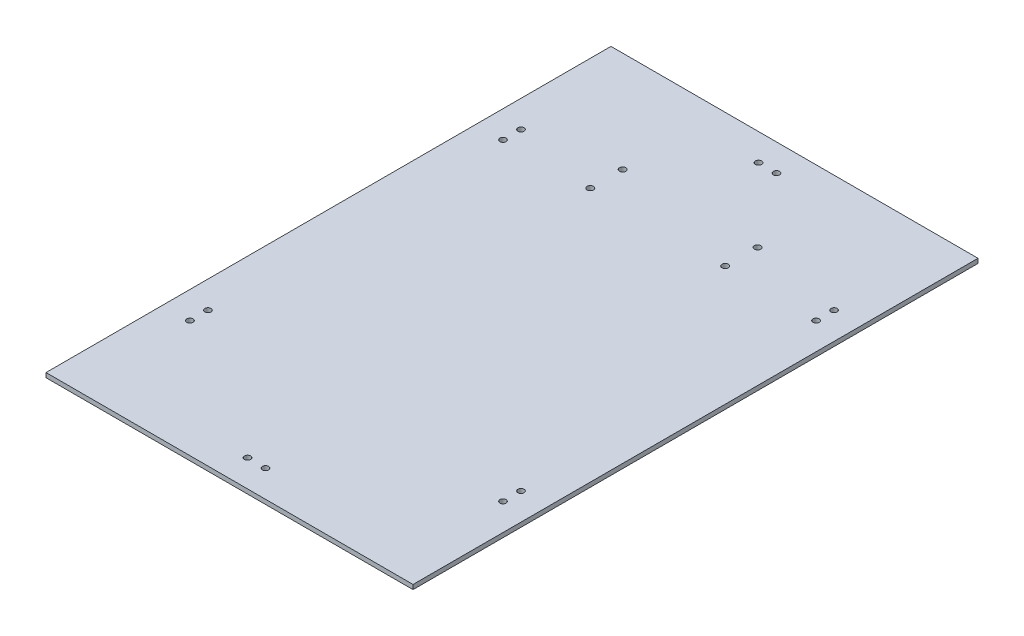
SolidWorks part; units mm, degrees
material "PC High Viscosity"
ref_plane "Front Plane" through (0, 0, 0) normal (0, 0, 1) x (1, 0, 0)
ref_plane "Top Plane" through (0, 0, 0) normal (0, 1, 0) x (1, 0, 0)
ref_plane "Right Plane" through (0, 0, 0) normal (1, 0, 0) x (0, 0, -1)
sketch "Sketch1" plane through (0, 0, 0) normal (0, 1, 0) x (1, 0, 0)
  line L1 (-154.0054, 230.8343) -> (105.0746, 230.8343)
  line L2 (-154.0054, 230.8343) -> (-154.0054, -167.9457)
  line L3 (-154.0054, -167.9457) -> (105.0746, -167.9457)
  line L4 (105.0746, 230.8343) -> (105.0746, -167.9457)
  point P0 (0, 0)
  dimension "D1" = 259.08
  dimension "D2" = 398.78
extrude "Boss-Extrude1" add sketch "Sketch1" along normal blind 3.175
sketch "Sketch18" plane through (0, 0, 0) normal (0, -1, 0) x (1, 0, 0)
  line L0 (-154.0054, -230.8343) -> (-154.0054, 167.9457) construction
  line L2 (-154.0054, 167.9457) -> (105.0746, 167.9457) construction
  point P0 (-74.6304, -136.8543)
  point P1 (20.6196, -136.8543)
  point P2 (20.6196, -159.7143)
  point P3 (-74.6304, -159.7143)
  dimension "D1" = 22.86
  dimension "D2" = 22.86
  dimension "D3" = 95.25
  dimension "D4" = 95.25
  dimension "D5" = 79.375
  dimension "D6" = 304.8
hole_wizard "#16 (0.177) Diameter Hole1" positions "Sketch19" profile "Sketch21" hole size "#16" standard "ANSI Inch" end condition through all
sketch "Sketch19" plane through (0, 0, 0) normal (0, -1, 0) x (-1, 0, 0)
  point P0 (-20.6196, 159.7143)
  point P3 (-20.6196, 136.8543)
  point P6 (74.6304, 136.8543)
  point P9 (74.6304, 159.7143)
sketch "Sketch21" plane through (20.6196, 0, -159.7143) normal (1, 0, 0) x (0, 0, -1)
  line L0 (0, 0) -> (0, 3.175)
  line L1 (0, 3.175) -> (2.2479, 3.175)
  line L2 (2.2479, 3.175) -> (2.2479, 0)
  line L5 (2.2479, 0) -> (0, 0)
  line L11 (0, -6.35) -> (0, 107.95) construction
  dimension "Thru Hole Dia." = 4.4958
  dimension "Thru Hole Depth" = 3.175
sketch "Sketch22" plane through (0, 0, 0) normal (0, -1, 0) x (1, 0, 0)
  line L0 (105.0746, -230.8343) -> (105.0746, 167.9457) construction
  line L1 (-154.0054, -230.8343) -> (-154.0054, 167.9457) construction
  line L2 (-154.0054, 167.9457) -> (105.0746, 167.9457) construction
  line L3 (-154.0054, -230.8343) -> (105.0746, -230.8343) construction
  point P0 (86.0246, 85.3957)
  point P1 (86.0246, -148.2843)
  point P2 (-134.9554, -148.2843)
  point P3 (-134.9554, 85.3957)
  point P4 (-18.1154, -211.7843)
  point P5 (-134.9554, 72.6957)
  point P6 (86.0246, 72.6957)
  point P7 (-134.9554, -135.5843)
  point P16 (-30.8154, -211.7843)
  point P17 (-30.8154, 148.8957)
  point P18 (86.0246, -135.5843)
  point P19 (-18.1154, 148.8957)
  dimension "D1" = 19.05
  dimension "D2" = 19.05
  dimension "D3" = 82.55
  dimension "D4" = 82.55
  dimension "D5" = 123.19
  dimension "D6" = 19.05
  dimension "D7" = 123.19
  dimension "D8" = 95.25
  dimension "D9" = 19.05
  dimension "D10" = 19.05
  dimension "D11" = 95.25
  dimension "D12" = 19.05
  dimension "D13" = 19.05
  dimension "D14" = 123.19
  dimension "D15" = 123.19
  dimension "D16" = 19.05
hole_wizard "11/64 (0.17188) Diameter Hole1" positions "Sketch23" profile "Sketch24" hole size "11/64" standard "ANSI Inch" end condition through all
sketch "Sketch23" plane through (0, 0, 0) normal (0, -1, 0) x (-1, 0, 0)
  point P0 (-86.0246, 148.2843)
  point P3 (30.8154, 211.7843)
  point P6 (134.9554, 148.2843)
  point P9 (134.9554, -85.3957)
  point P12 (18.1154, 211.7843)
  point P15 (-86.0246, -85.3957)
  point P18 (134.9554, -72.6957)
  point P21 (134.9554, 135.5843)
  point P24 (-86.0246, 135.5843)
  point P27 (-86.0246, -72.6957)
  point P31 (18.1154, -148.8957)
  point P34 (30.8154, -148.8957)
sketch "Sketch24" plane through (86.0246, 0, -148.2843) normal (1, 0, 0) x (0, 0, -1)
  line L0 (0, 0) -> (0, 3.175)
  line L1 (0, 3.175) -> (2.1829, 3.175)
  line L2 (2.1829, 3.175) -> (2.1829, 0)
  line L5 (2.1829, 0) -> (0, 0)
  line L11 (0, -6.35) -> (0, 107.95) construction
  dimension "Thru Hole Dia." = 4.3658
  dimension "Thru Hole Depth" = 3.175
